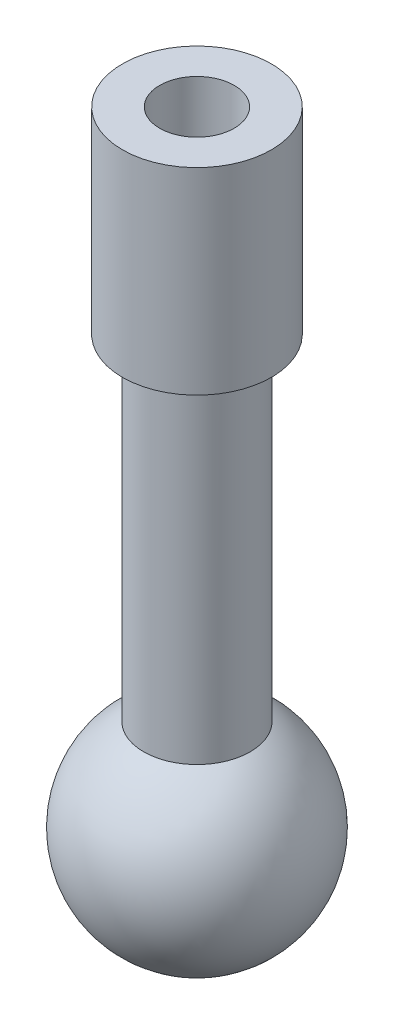
SolidWorks part; units mm, degrees
ref_plane "Front Plane" through (0, 0, 0) normal (0, 0, 1) x (1, 0, 0)
ref_plane "Top Plane" through (0, 0, 0) normal (0, 1, 0) x (1, 0, 0)
ref_plane "Right Plane" through (0, 0, 0) normal (1, 0, 0) x (0, 0, -1)
sketch "Sketch1" plane through (0, 0, 0) normal (0, 0, 1) x (1, 0, 0)
  line L0 (0, 41.7343) -> (0, -26.926) construction
  line L1 (0, 41.7343) -> (5, 41.7343)
  line L2 (5, 41.7343) -> (5, -8.2657)
  line L3 (0, 41.7343) -> (0, -26.926)
  arc A0 (5, -8.2657) -> (0, -26.926) centre (0, -16.926) cw
  dimension "D1" = 10
  dimension "D2" = 5
  dimension "D3" = 50
revolve "Revolve1" add sketch "Sketch1" angle 360 about L0
sketch "Sketch3" plane through (0, 0, 0) normal (0, 0, 1) x (1, 0, 0)
  line L0 (0, 41.7343) -> (0, 23.214) construction
  line L1 (5, 41.7343) -> (-5, 41.7343) construction
  line L2 (0, 23.214) -> (7, 23.214)
  line L3 (0, 41.7343) -> (0, 23.214)
  line L4 (7, 23.214) -> (7, 41.7343)
  line L5 (7, 41.7343) -> (0, 41.7343)
  line L6 (0, 41.7343) -> (0, 23.214) construction
  dimension "D1" = 7
revolve "Revolve3" add sketch "Sketch3" angle 360 about L0
sketch "Sketch4" plane through (0, 41.7343, 0) normal (0, 1, 0) x (1, 0, 0)
  circle A0 centre (0, 0) radius 3.5
  dimension "D1" = 7
extrude "Cut-Extrude1" cut sketch "Sketch4" against normal blind 5
